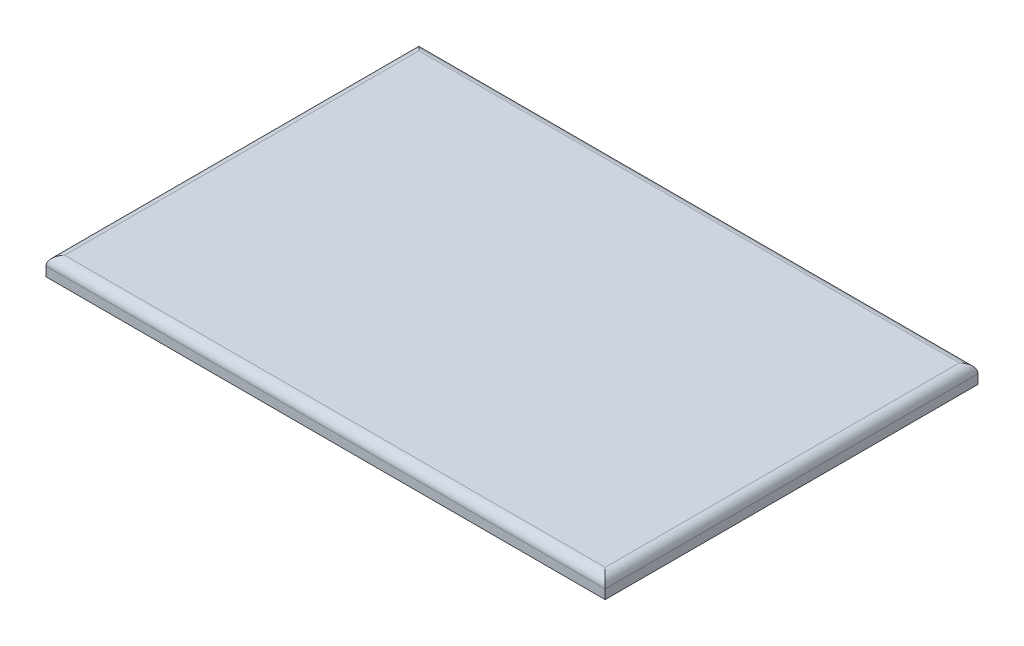
SolidWorks part; units mm, degrees
ref_plane "Ebene vorne" through (0, 0, 0) normal (0, 0, 1) x (1, 0, 0)
ref_plane "Ebene oben" through (0, 0, 0) normal (0, 1, 0) x (1, 0, 0)
ref_plane "Ebene rechts" through (0, 0, 0) normal (1, 0, 0) x (0, 0, -1)
sketch "Sketch1" plane through (0, 0, 0) normal (0, 1, 0) x (1, 0, 0)
  line L1 (-30, 20) -> (30, 20)
  line L2 (-30, 20) -> (-30, -20)
  line L3 (-30, -20) -> (30, -20)
  line L4 (30, 20) -> (30, -20)
  line L5 (-30, 20) -> (30, -20) construction
  line L6 (-30, -20) -> (30, 20) construction
  point P0 (0, 0)
  dimension "D1" = 40
  dimension "D2" = 60
extrude "Boss-Extrude1" add sketch "Sketch1" along normal blind 2
sketch "Sketch2" plane through (0, 0, 0) normal (0, 1, 0) x (1, 0, 0)
  line L1 (-28.5, 18.5) -> (28.5, 18.5)
  line L2 (-28.5, 18.5) -> (-28.5, -18.5)
  line L3 (-28.5, -18.5) -> (28.5, -18.5)
  line L4 (28.5, 18.5) -> (28.5, -18.5)
  line L5 (-28.5, 18.5) -> (28.5, -18.5) construction
  line L6 (-28.5, -18.5) -> (28.5, 18.5) construction
  point P0 (0, 0)
  dimension "D1" = 57
  dimension "D2" = 37
extrude "Boss-Extrude2" add sketch "Sketch2" against normal blind 2
fillet "Fillet1" radius 1 4 edges at (0, 2, 20) (-30, 2, 0) (0, 2, -20) (30, 2, 0)
fillet "Fillet2" radius 1 4 edges at (0, -2, -18.5) (-28.5, -2, 0) (0, -2, 18.5) (28.5, -2, 0)
